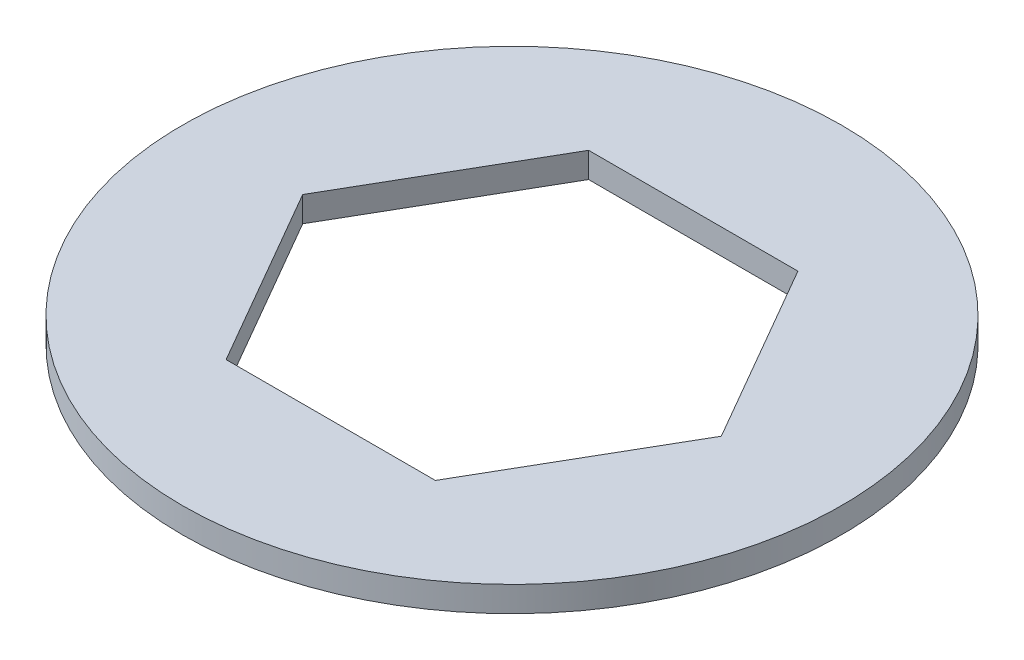
SolidWorks part; units mm, degrees
ref_plane "Ebene vorne" through (0, 0, 0) normal (0, 0, 1) x (1, 0, 0)
ref_plane "Ebene oben" through (0, 0, 0) normal (0, 1, 0) x (1, 0, 0)
ref_plane "Ebene rechts" through (0, 0, 0) normal (1, 0, 0) x (0, 0, -1)
sketch "Skizze1" plane through (0, 0, 0) normal (0, 1, 0) x (1, 0, 0)
  line L0 (0, 0) -> (41.2805, 0) construction
  line L1 (41.2805, 0) -> (20.6403, 35.75)
  line L2 (20.6403, 35.75) -> (-20.6403, 35.75)
  line L3 (-20.6403, 35.75) -> (-41.2805, 0)
  line L4 (-41.2805, 0) -> (-20.6403, -35.75)
  line L5 (-20.6403, -35.75) -> (20.6403, -35.75)
  line L6 (20.6403, -35.75) -> (41.2805, 0)
  circle A0 centre (0, 0) radius 35.75 construction
  circle A1 centre (0, 0) radius 65
  dimension "D1" = 71.5
  dimension "D2" = 130
extrude "Aufsatz-Linear austragen1" add sketch "Skizze1" along normal blind 5
